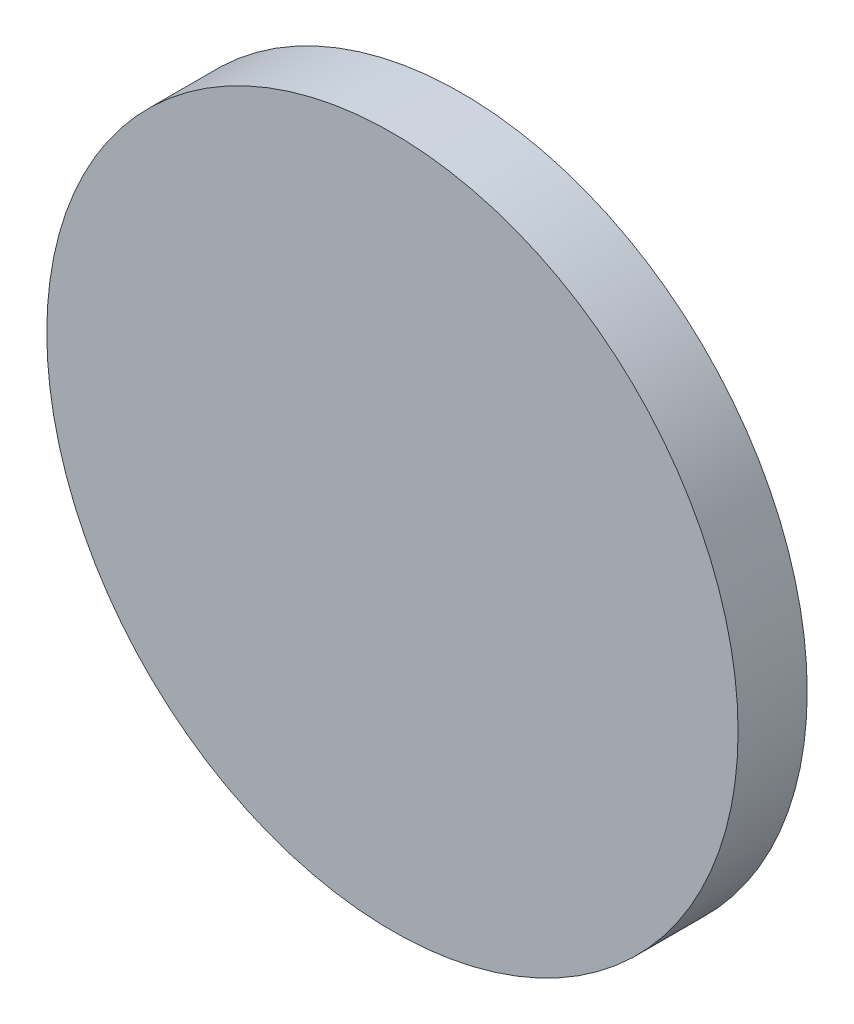
SolidWorks part; units mm, degrees
ref_plane "Front Plane" through (0, 0, 0) normal (0, 0, 1) x (1, 0, 0)
ref_plane "Top Plane" through (0, 0, 0) normal (0, 1, 0) x (1, 0, 0)
ref_plane "Right Plane" through (0, 0, 0) normal (1, 0, 0) x (0, 0, -1)
sketch "Sketch1" plane through (0, 0, 0) normal (0, 0, 1) x (1, 0, 0)
  circle A0 centre (0, 0) radius 10
  dimension "D1" = 20
extrude "Boss-Extrude1" add sketch "Sketch1" along normal blind 2
